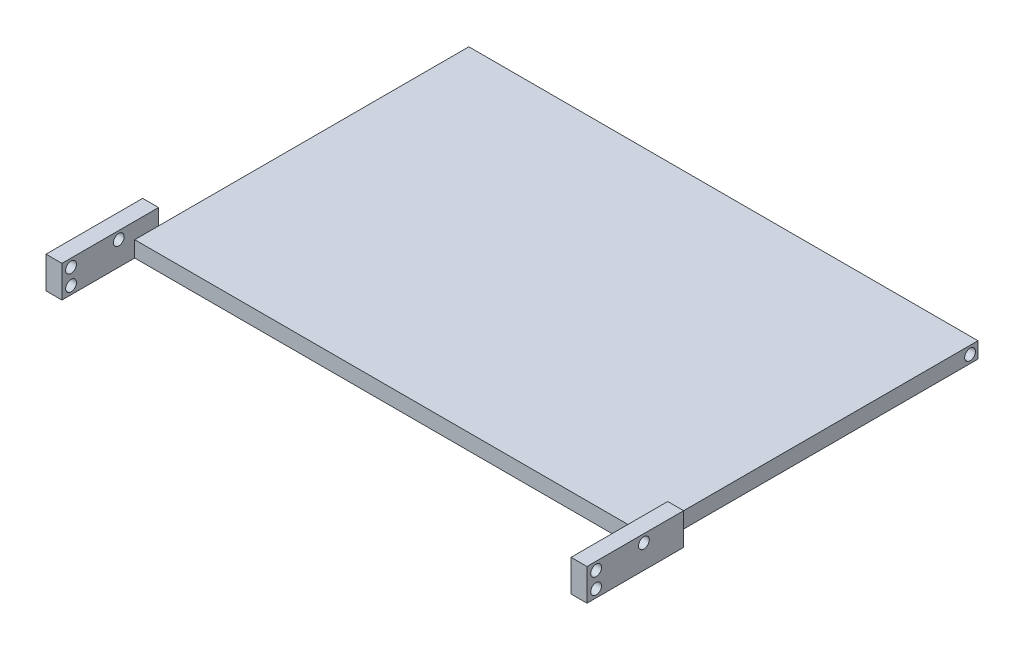
SolidWorks part; units mm, degrees
material "ABS PC"
ref_plane "前视基准面" through (0, 0, 0) normal (0, 0, 1) x (1, 0, 0)
ref_plane "上视基准面" through (0, 0, 0) normal (0, 1, 0) x (1, 0, 0)
ref_plane "右视基准面" through (0, 0, 0) normal (1, 0, 0) x (0, 0, -1)
other "Configuration Table"
sketch "草图1" plane through (0, 0, 0) normal (0, 1, 0) x (1, 0, 0)
  line L1 (-80, 52.5) -> (80, 52.5)
  line L2 (-80, 52.5) -> (-80, -52.5)
  line L3 (-80, -52.5) -> (80, -52.5)
  line L4 (80, 52.5) -> (80, -52.5)
  line L5 (-80, 52.5) -> (80, -52.5) construction
  line L6 (-80, -52.5) -> (80, 52.5) construction
  point P0 (0, 0)
  dimension "D1" = 160
  dimension "D2" = 105
extrude "凸台-拉伸1" add sketch "草图1" along normal blind 5
sketch "草图3" plane through (80, 0, 0) normal (1, 0, 0) x (0, 0, -1)
  line L1 (-52.5, 0) -> (52.5, 0) construction
  line L3 (-45, 0) -> (-75.377, 0)
  line L4 (-45, 0) -> (-45, 10)
  line L5 (-45, 10) -> (-75.377, 10)
  line L6 (-75.377, 0) -> (-75.377, 10)
  point P8 (0, 0)
  dimension "D1" = 10
extrude "凸台-拉伸3" add sketch "草图3" along normal blind 5 contours L6 L5 L4 L3
sketch "草图4" plane through (-80, 0, 0) normal (-1, 0, 0) x (0, 0, 1)
  line L2 (75.377, 0) -> (75.377, 10) construction
  line L3 (45, 0) -> (75.377, 0)
  line L4 (45, 0) -> (45, 10)
  line L5 (45, 10) -> (75.377, 10)
  line L6 (75.377, 0) -> (75.377, 10)
  line L7 (45, 10) -> (75.377, 10) construction
  point P14 (73.8456, 9.1162)
  point P15 (45, 5)
extrude "凸台-拉伸4" add sketch "草图4" along normal blind 5 contours L5 L6 L3 L4
sketch "草图5" plane through (-80, 0, 0) normal (-1, 0, 0) x (0, 0, 1)
  circle A0 centre (-50, 2.5) radius 1.7
  point P2 (59.0765, 9.827)
sketch "草图6" plane through (-85, 0, 0) normal (-1, 0, 0) x (0, 0, 1)
  circle A0 centre (57.5, 7.5) radius 1.7
  circle A1 centre (72.5, 7.5) radius 1.7
  point P2 (0, 0)
extrude "切除-拉伸1" cut sketch "草图5" against normal blind 200 contours A0
extrude "切除-拉伸3" cut sketch "草图6" against normal blind 200 contours A1 | A0
sketch "草图7" plane through (85, 0, 0) normal (1, 0, 0) x (0, 0, -1)
  circle A0 centre (-72.5, 2.5) radius 1.7
extrude "切除-拉伸4" cut sketch "草图7" against normal blind 200
